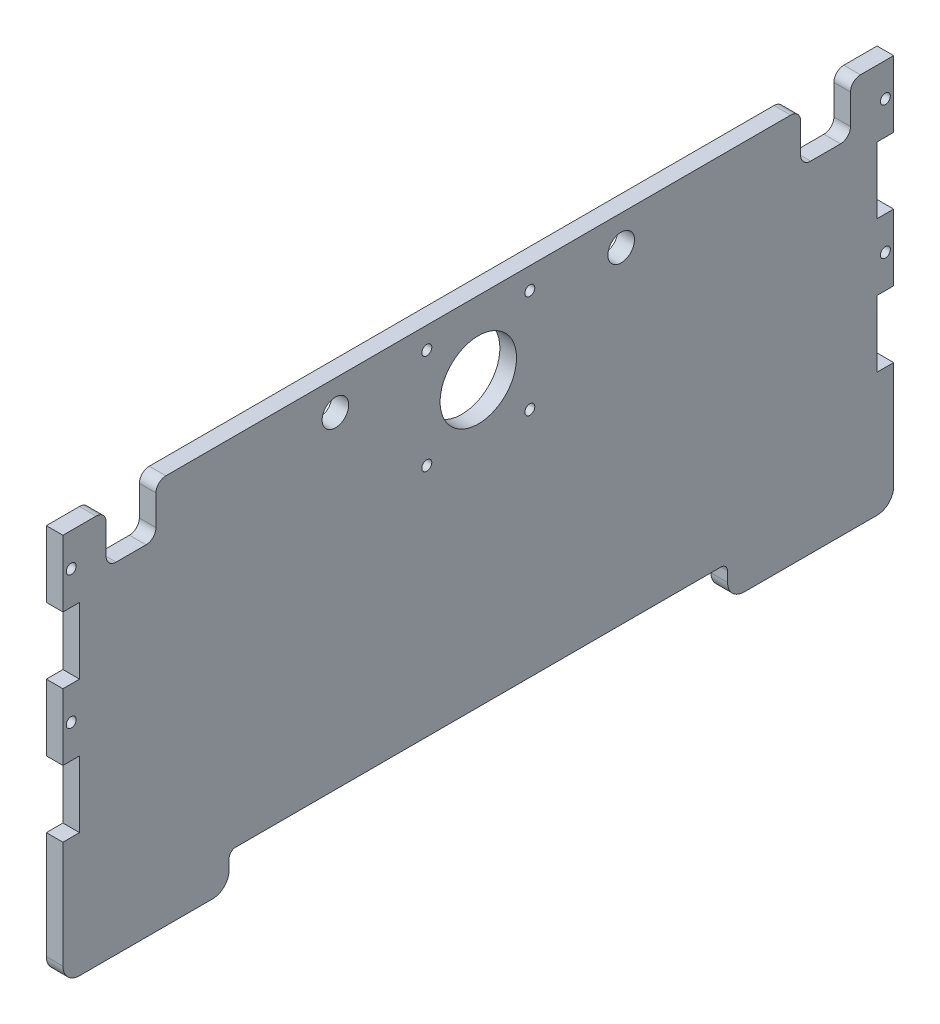
SolidWorks part; units mm, degrees
ref_plane "前视基准面" through (0, 0, 0) normal (0, 0, 1) x (1, 0, 0)
ref_plane "上视基准面" through (0, 0, 0) normal (0, 1, 0) x (1, 0, 0)
ref_plane "右视基准面" through (0, 0, 0) normal (1, 0, 0) x (0, 0, -1)
sketch "草图1" plane through (0, 0, 0) normal (1, 0, 0) x (0, 0, -1)
  line L0 (-69.7464, -6.9122) -> (-69.7464, -3.9122)
  line L1 (-114.7464, -11.9122) -> (-74.7464, -11.9122)
  line L2 (-119.7464, -6.9122) -> (-119.7464, 25.3878)
  line L3 (-119.7464, 105.3878) -> (-109.7464, 105.3878)
  line L4 (130.2536, -6.9122) -> (130.2536, 25.3878)
  line L5 (-67.7464, -1.9122) -> (78.2536, -1.9122)
  line L6 (80.2536, -3.9122) -> (80.2536, -6.9122)
  line L7 (-114.7464, 126.8168) -> (-114.7464, -7.6613) construction
  line L8 (125.2536, 118.7303) -> (125.2536, -7.6613) construction
  line L9 (85.2536, -11.9122) -> (125.2536, -11.9122)
  line L10 (-119.7464, 85.3878) -> (-114.7464, 85.3878)
  line L11 (-114.7464, 85.3878) -> (-114.7464, 65.3878)
  line L12 (-114.7464, 65.3878) -> (-119.7464, 65.3878)
  line L13 (-119.7464, 45.3878) -> (-114.7464, 45.3878)
  line L14 (-114.7464, 45.3878) -> (-114.7464, 25.3878)
  line L15 (-114.7464, 25.3878) -> (-119.7464, 25.3878)
  line L16 (125.2536, 85.3878) -> (130.2536, 85.3878)
  line L17 (5.2536, 152.4788) -> (5.2536, -24.4058) construction
  line L18 (130.2536, 65.3878) -> (125.2536, 65.3878)
  line L19 (125.2536, 65.3878) -> (125.2536, 85.3878)
  line L20 (-119.7464, 85.3878) -> (-119.7464, 105.3878)
  line L21 (125.2536, 45.3878) -> (130.2536, 45.3878)
  line L22 (125.2536, 45.3878) -> (125.2536, 25.3878)
  line L23 (125.2536, 25.3878) -> (130.2536, 25.3878)
  line L24 (130.2536, 85.3878) -> (130.2536, 105.3878)
  line L25 (-119.7464, 45.3878) -> (-119.7464, 65.3878)
  line L26 (130.2536, 45.3878) -> (130.2536, 65.3878)
  line L27 (109.7536, 132.6414) -> (109.7536, -30.7663) construction
  line L28 (-99.2464, 132.6414) -> (-99.2464, -28.5496) construction
  line L29 (120.2536, 105.3878) -> (130.2536, 105.3878)
  line L30 (-88.7464, 105.3878) -> (99.2536, 105.3878)
  line L31 (117.2536, 102.3878) -> (117.2536, 93.3878)
  line L32 (114.2536, 90.3878) -> (105.2536, 90.3878)
  line L33 (102.2536, 102.3878) -> (102.2536, 93.3878)
  line L34 (127.7536, 110.6729) -> (127.7536, -24.4058) construction
  line L35 (-91.7464, 102.3878) -> (-91.7464, 93.3878)
  line L36 (-94.7464, 90.3878) -> (-103.7464, 90.3878)
  line L37 (-106.7464, 102.3878) -> (-106.7464, 93.3878)
  line L38 (-117.2464, 107.8878) -> (-117.2464, -22.2251) construction
  circle A0 centre (48.2536, 96.3878) radius 4
  circle A1 centre (-37.7464, 96.3878) radius 4
  circle A2 centre (5.2536, 83.3878) radius 11.5
  circle A3 centre (-10.2464, 98.8878) radius 1.5
  circle A4 centre (20.7536, 98.8878) radius 1.5
  circle A5 centre (20.7536, 67.8878) radius 1.5
  circle A6 centre (-10.2464, 68.825) radius 1.5
  arc A7 (-114.7464, -11.9122) -> (-119.7464, -6.9122) centre (-114.7464, -6.9122) cw
  arc A8 (-69.7464, -6.9122) -> (-74.7464, -11.9122) centre (-74.7464, -6.9122) cw
  arc A9 (125.2536, -11.9122) -> (130.2536, -6.9122) centre (125.2536, -6.9122) ccw
  arc A10 (80.2536, -6.9122) -> (85.2536, -11.9122) centre (85.2536, -6.9122) ccw
  arc A11 (-69.7464, -3.9122) -> (-67.7464, -1.9122) centre (-67.7464, -3.9122) cw
  arc A12 (78.2536, -1.9122) -> (80.2536, -3.9122) centre (78.2536, -3.9122) cw
  arc A13 (-91.7464, 93.3878) -> (-94.7464, 90.3878) centre (-94.7464, 93.3878) cw
  arc A14 (-103.7464, 90.3878) -> (-106.7464, 93.3878) centre (-103.7464, 93.3878) cw
  arc A15 (-109.7464, 105.3878) -> (-106.7464, 102.3878) centre (-109.7464, 102.3878) cw
  arc A16 (-88.7464, 105.3878) -> (-91.7464, 102.3878) centre (-88.7464, 102.3878) ccw
  arc A17 (117.2536, 93.3878) -> (114.2536, 90.3878) centre (114.2536, 93.3878) cw
  arc A18 (105.2536, 90.3878) -> (102.2536, 93.3878) centre (105.2536, 93.3878) cw
  arc A19 (99.2536, 105.3878) -> (102.2536, 102.3878) centre (99.2536, 102.3878) cw
  arc A20 (120.2536, 105.3878) -> (117.2536, 102.3878) centre (120.2536, 102.3878) ccw
  circle A21 centre (127.7536, 95.3878) radius 1.5
  circle A22 centre (127.7536, 55.3878) radius 1.5
  circle A23 centre (-117.2464, 95.3878) radius 1.5
  circle A24 centre (-117.2464, 55.3878) radius 1.5
  point P49 (-119.7464, -11.9122)
  point P54 (130.2536, -11.9122)
  point P57 (80.2536, -11.9122)
  point P73 (-91.7464, 90.3878)
  point P76 (-106.7464, 90.3878)
  point P81 (-91.7464, 105.3878)
  point P84 (117.2536, 90.3878)
  point P87 (102.2536, 90.3878)
  point P90 (102.2536, 105.3878)
  point P93 (117.2536, 105.3878)
  dimension "D17" = 8
  dimension "D18" = 8
  dimension "D19" = 23
  dimension "D26" = 3
  dimension "D27" = 3
  dimension "D28" = 3
  dimension "D29" = 3
  dimension "D36" = 5
  dimension "D37" = 2
  dimension "D47" = 3
  dimension "D51" = 10
  dimension "D52" = 10
  dimension "D53" = 10
  dimension "D54" = 10
  dimension "D1" = 5
  dimension "D2" = 5
  dimension "D3" = 10
  dimension "D4" = 117.3
  dimension "D5" = 250
  dimension "D6" = 50
  dimension "D7" = 50
  dimension "D8" = 20
  dimension "D9" = 20
  dimension "D10" = 20
  dimension "D11" = 20
  dimension "D12" = 37.3
  dimension "D13" = 20
  dimension "D14" = 20
  dimension "D15" = 20
  dimension "D16" = 20
  dimension "D20" = 9
  dimension "D21" = 9
  dimension "D22" = 22
  dimension "D23" = 125
  dimension "D24" = 43
  dimension "D25" = 43
  dimension "D30" = 31
  dimension "D31" = 31
  dimension "D32" = 31
  dimension "D33" = 15.5
  dimension "D34" = 15.5
  dimension "D35" = 15.5
  dimension "D38" = 209
  dimension "D39" = 250
  dimension "D40" = 20.5
  dimension "D41" = 15
  dimension "D42" = 15
  dimension "D43" = 15
  dimension "D44" = 15
  dimension "D45" = 7.5
  dimension "D46" = 7.5
  dimension "D48" = 2.5
  dimension "D49" = 2.5
  dimension "D50" = 2.5
extrude "凸台-拉伸1" add sketch "草图1" along normal blind 5
